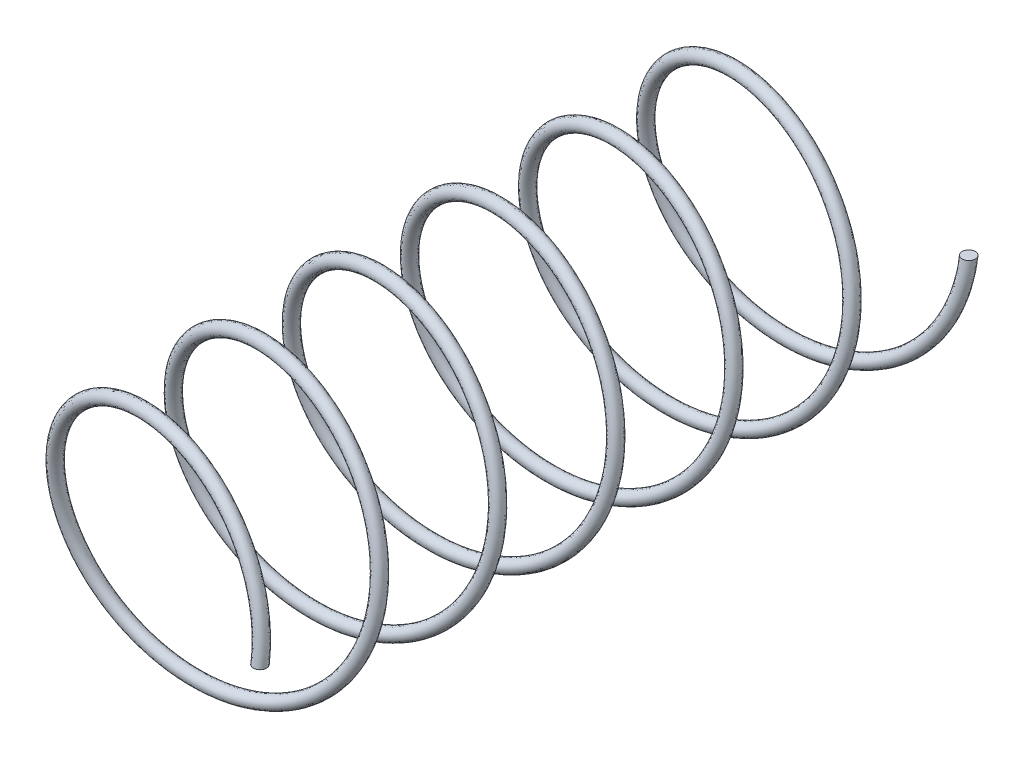
SolidWorks part; units mm, degrees
ref_plane "前视基准面" through (0, 0, 0) normal (0, 0, 1) x (1, 0, 0)
ref_plane "上视基准面" through (0, 0, 0) normal (0, 1, 0) x (1, 0, 0)
ref_plane "右视基准面" through (0, 0, 0) normal (1, 0, 0) x (0, 0, -1)
other "Configuration Table"
sketch "草图5" plane through (0, 0, 0) normal (0, 0, 1) x (1, 0, 0)
  circle A0 centre (0, 0) radius 5
  dimension "D1" = 10
curve "螺旋线/涡状线1" pitch 4.5 height 27 turns 6
sketch "草图11" plane through (0, 0, 0) normal (0, 1, 0) x (1, 0, 0)
  circle A0 centre (5, -27) radius 0.25
  spline S0 degree 3 poles (5, 0) (5, -0.0932) (4.7397, -0.2815) (3.6276, -0.5624) (1.9632, -0.8438) (0, -1.125) (-1.9632, -1.4063) (-3.6276, -1.6875) (-4.7397, -1.9688) (-5.1302, -2.25) (-4.7397, -2.5313) (-3.6276, -2.8125) (-1.4084, -3.1875) (1.4084, -3.5625) (3.6276, -3.9375) (4.7397, -4.2188) (5.1302, -4.5) (4.7397, -4.7813) (3.6276, -5.0625) (1.4084, -5.4375) (-1.4084, -5.8125) (-3.6276, -6.1875) (-4.7397, -6.4688) (-5.1302, -6.75) (-4.7397, -7.0313) (-3.6276, -7.3125) (-1.4084, -7.6875) (1.4084, -8.0625) (3.6276, -8.4375) (4.7397, -8.7188) (5.1302, -9) (4.7397, -9.2813) (3.6276, -9.5625) (1.4084, -9.9375) (-1.4084, -10.3125) (-3.6276, -10.6875) (-4.7397, -10.9688) (-5.1302, -11.25) (-4.7397, -11.5313) (-3.6276, -11.8125) (-1.4084, -12.1875) (1.4084, -12.5625) (3.6276, -12.9375) (4.7397, -13.2188) (5.1302, -13.5) (4.7397, -13.7813) (3.6276, -14.0625) (1.4084, -14.4375) (-1.4084, -14.8125) (-3.6276, -15.1875) (-4.7397, -15.4688) (-5.1302, -15.75) (-4.7397, -16.0313) (-3.6276, -16.3125) (-1.4084, -16.6875) (1.4084, -17.0625) (3.6276, -17.4375) (4.7397, -17.7188) (5.1302, -18) (4.7397, -18.2813) (3.6276, -18.5625) (1.4084, -18.9375) (-1.4084, -19.3125) (-3.6276, -19.6875) (-4.7397, -19.9688) (-5.1302, -20.25) (-4.7397, -20.5313) (-3.6276, -20.8125) (-1.4084, -21.1875) (1.4084, -21.5625) (3.6276, -21.9375) (4.7397, -22.2187) (5.1302, -22.5) (4.7397, -22.7812) (3.6276, -23.0625) (1.4084, -23.4375) (-1.4084, -23.8125) (-3.6276, -24.1875) (-4.7397, -24.4687) (-5.1302, -24.75) (-4.7397, -25.0312) (-3.6276, -25.3125) (-1.9632, -25.5937) (0, -25.875) (1.9632, -26.1562) (3.6276, -26.4376) (4.7397, -26.7185) (5, -26.9068) (5, -27) knots 0 0 0 0 0.010417 0.020833 0.03125 0.041667 0.052083 0.0625 0.072917 0.083333 0.09375 0.104167 0.114583 0.135417 0.145833 0.15625 0.166667 0.177083 0.1875 0.197917 0.21875 0.229167 0.239583 0.25 0.260417 0.270833 0.28125 0.302083 0.3125 0.322917 0.333333 0.34375 0.354167 0.364583 0.385417 0.395833 0.40625 0.416667 0.427083 0.4375 0.447917 0.46875 0.479167 0.489583 0.5 0.510417 0.520833 0.53125 0.552083 0.5625 0.572917 0.583333 0.59375 0.604167 0.614583 0.635417 0.645833 0.65625 0.666667 0.677083 0.6875 0.697917 0.71875 0.729167 0.739583 0.75 0.760417 0.770833 0.78125 0.802083 0.8125 0.822917 0.833333 0.84375 0.854167 0.864583 0.885417 0.895833 0.90625 0.916667 0.927083 0.9375 0.947917 0.958333 0.96875 0.979167 0.989583 1 1 1 1 construction
  dimension "D1" = 0.5
sweep "扫描2" add profiles "草图11" path "螺旋线/涡状线1"
